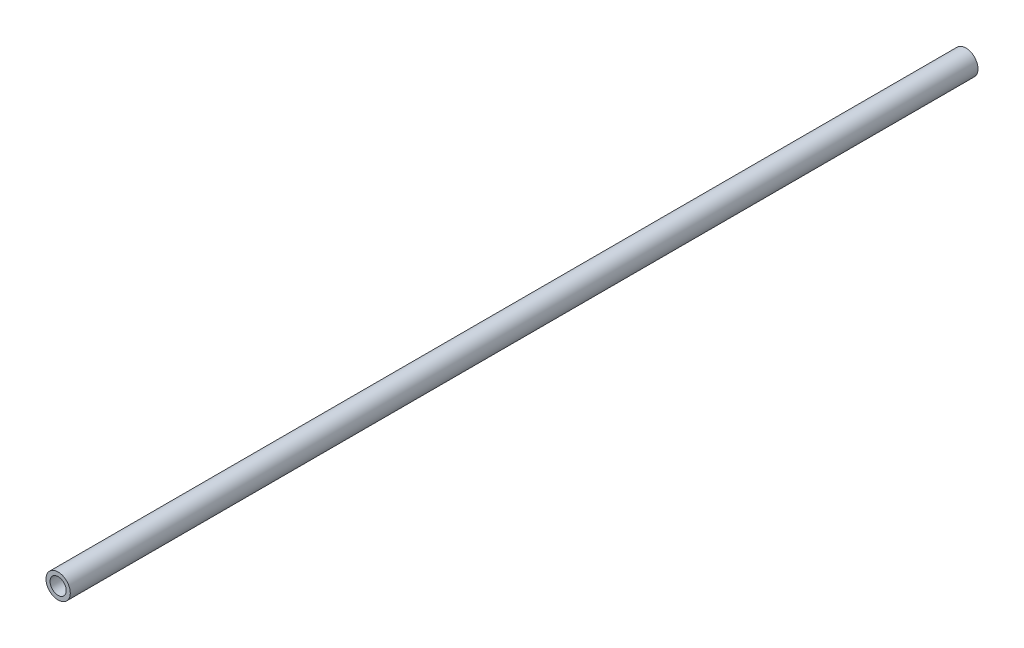
SolidWorks part; units mm, degrees
ref_plane "Front Plane" through (0, 0, 0) normal (0, 0, 1) x (1, 0, 0)
ref_plane "Top Plane" through (0, 0, 0) normal (0, 1, 0) x (1, 0, 0)
ref_plane "Right Plane" through (0, 0, 0) normal (1, 0, 0) x (0, 0, -1)
sketch "Sketch2" plane through (0, 0, 0) normal (0, 0, 1) x (1, 0, 0)
  circle A0 centre (0, 0) radius 7.5
  circle A1 centre (0, 0) radius 5
extrude "Boss-Extrude1" add sketch "Sketch2" along normal blind 560
